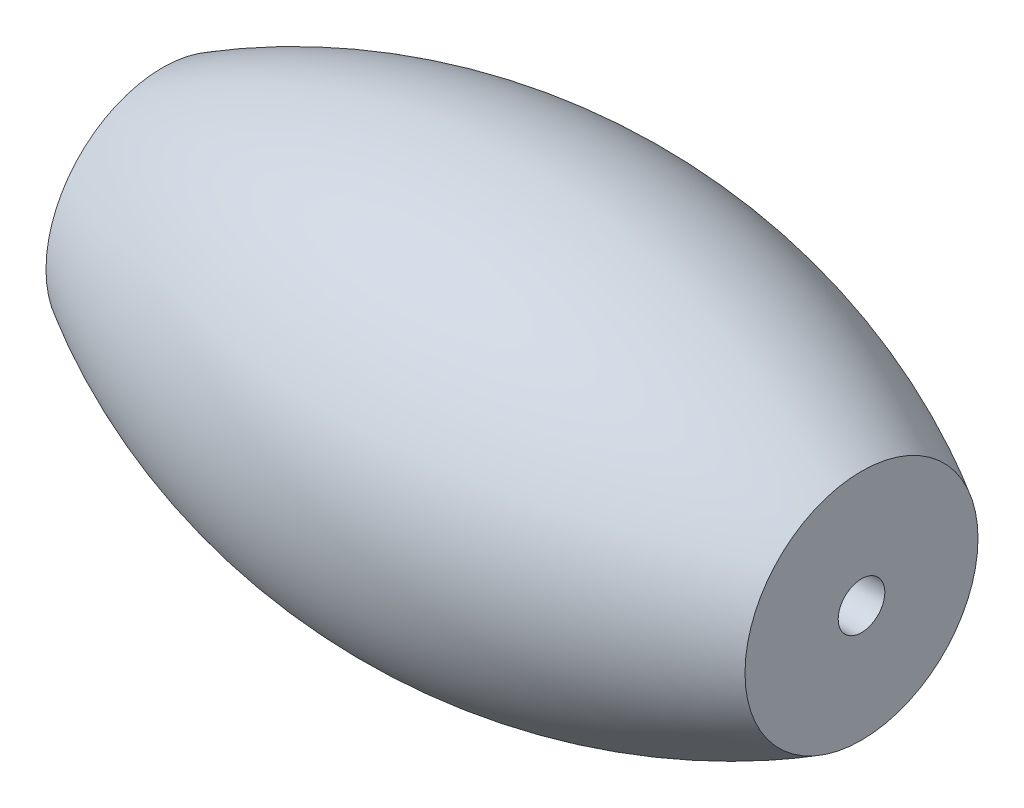
SolidWorks part; units mm, degrees
material "Rubber"
ref_plane "Front Plane" through (0, 0, 0) normal (0, 0, 1) x (1, 0, 0)
ref_plane "Top Plane" through (0, 0, 0) normal (0, 1, 0) x (1, 0, 0)
ref_plane "Right Plane" through (0, 0, 0) normal (1, 0, 0) x (0, 0, -1)
sketch "Sketch1" plane through (0, 0, 0) normal (0, 1, 0) x (1, 0, 0)
  line L0 (-15, 0) -> (15, 0) construction
  line L1 (-15, 0) -> (-15, 5)
  line L2 (15, 5) -> (15, 0)
  line L3 (-15, 5) -> (0, -20.9808) construction
  line L4 (0, -20.9808) -> (15, 5) construction
  line L5 (0, 0) -> (0, -20.9808) construction
  line L6 (-15, 1) -> (15, 1)
  arc A0 (-15, 5) -> (15, 5) centre (0, -20.9808) cw
  dimension "D1" = 30
  dimension "D2" = 60
  dimension "D3" = 5
  dimension "D4" = 1
revolve "Revolve3" add sketch "Sketch1" angle 360 about L0
